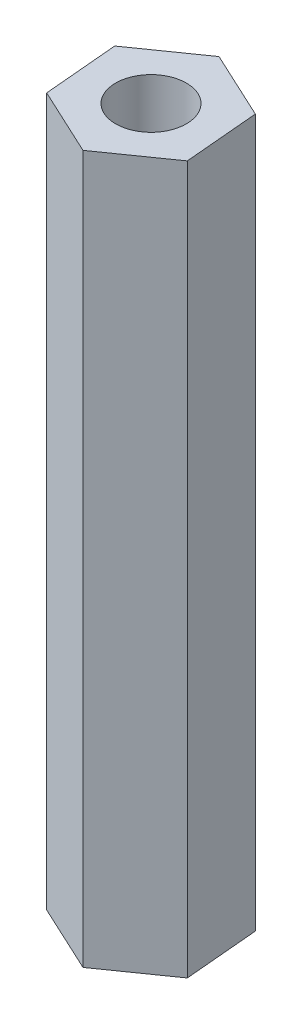
SolidWorks part; units mm, degrees
ref_plane "前视基准面" through (0, 0, 0) normal (0, 0, 1) x (1, 0, 0)
ref_plane "上视基准面" through (0, 0, 0) normal (0, 1, 0) x (1, 0, 0)
ref_plane "右视基准面" through (0, 0, 0) normal (1, 0, 0) x (0, 0, -1)
sketch "草图1" plane through (0, 0, 0) normal (0, 1, 0) x (1, 0, 0)
  line L1 (2.8788, -1.34) -> (2.5999, 1.8231)
  line L2 (2.5999, 1.8231) -> (-0.2789, 3.1632)
  line L3 (-0.2789, 3.1632) -> (-2.8788, 1.34)
  line L4 (-2.8788, 1.34) -> (-2.5999, -1.8231)
  line L5 (-2.5999, -1.8231) -> (0.2789, -3.1632)
  line L6 (0.2789, -3.1632) -> (2.8788, -1.34)
  circle A0 centre (0, 0) radius 2.75 construction
  circle A1 centre (0, 0) radius 1.5
extrude "凸台-拉伸1" add sketch "草图1" along normal blind 30
